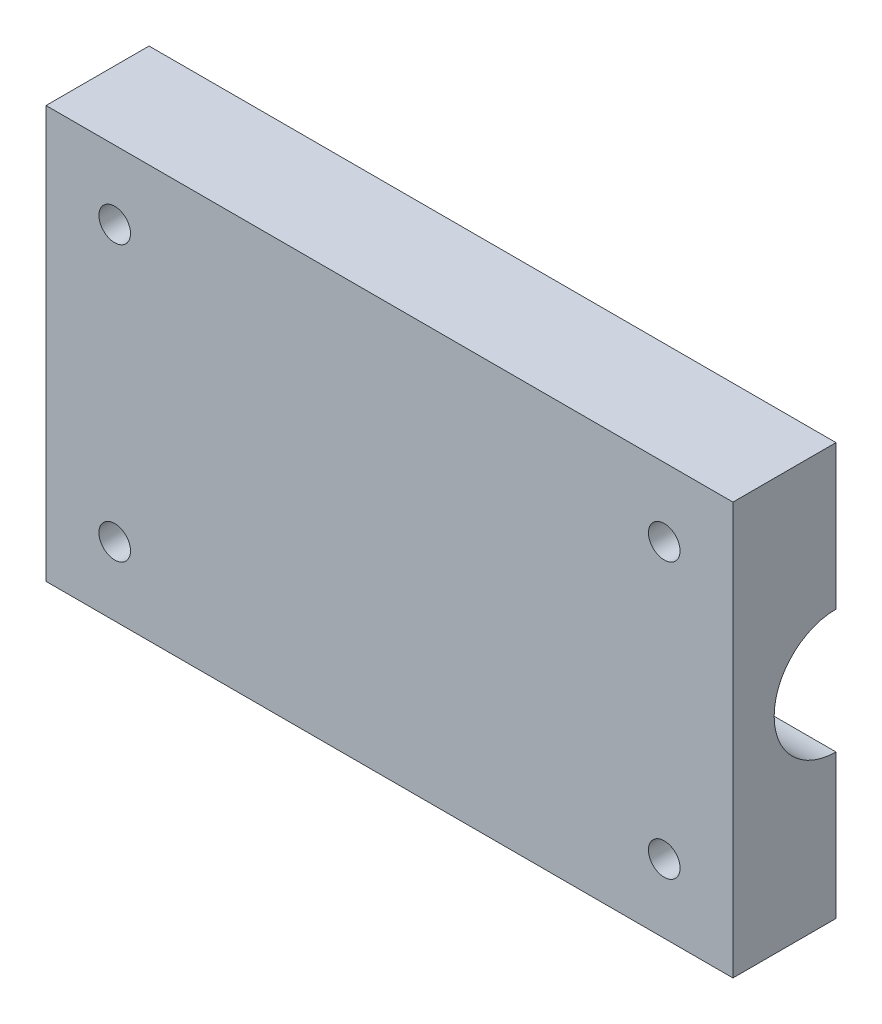
SolidWorks part; units mm, degrees
ref_plane "Front Plane" through (0, 0, 0) normal (0, 0, 1) x (1, 0, 0)
ref_plane "Top Plane" through (0, 0, 0) normal (0, 1, 0) x (1, 0, 0)
ref_plane "Right Plane" through (0, 0, 0) normal (1, 0, 0) x (0, 0, -1)
sketch "Sketch1" plane through (0, 0, 0) normal (0, 0, 1) x (1, 0, 0)
  line L0 (0, -55) -> (0, 55) construction
  line L1 (-50, 30) -> (50, 30)
  line L2 (-50, 30) -> (-50, -30)
  line L3 (-50, -30) -> (50, -30)
  line L4 (50, 30) -> (50, -30)
  line L5 (-50, 30) -> (50, -30) construction
  line L6 (-50, -30) -> (50, 30) construction
  line L7 (55, 0) -> (-55, 0) construction
  circle A0 centre (-40, -20) radius 2.3
  circle A1 centre (40, -20) radius 2.3
  circle A2 centre (40, 20) radius 2.3
  circle A3 centre (-40, 20) radius 2.3
  point P0 (0, 0)
  dimension "D3" = 4.6
  dimension "D1" = 60
  dimension "D2" = 100
  dimension "D4" = 10
  dimension "D5" = 10
extrude "Boss-Extrude1" add sketch "Sketch1" along normal blind 15
sketch "Sketch2" plane through (-50, 0, 0) normal (-1, 0, 0) x (0, 0, 1)
  circle A0 centre (0, 0) radius 9
  dimension "D1" = 18
extrude "Cut-Extrude1" cut sketch "Sketch2" against normal mid plane 400
